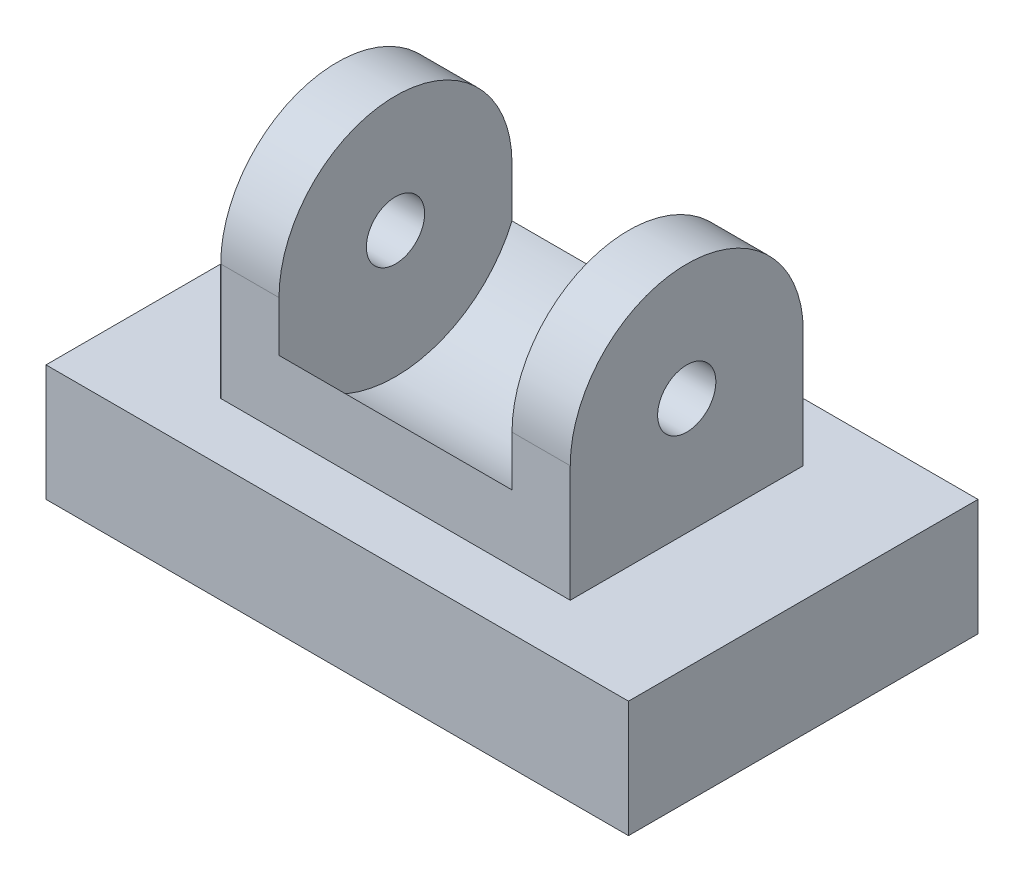
SolidWorks part; units mm, degrees
ref_plane "Plan de face" through (0, 0, 0) normal (0, 0, 1) x (1, 0, 0)
ref_plane "Plan de dessus" through (0, 0, 0) normal (0, 1, 0) x (1, 0, 0)
ref_plane "Plan de droite" through (0, 0, 0) normal (1, 0, 0) x (0, 0, -1)
sketch "Esquisse1" plane through (0, 0, 0) normal (0, 1, 0) x (1, 0, 0)
  line L1 (25, 15) -> (-25, 15)
  line L2 (25, 15) -> (25, -15)
  line L3 (25, -15) -> (-25, -15)
  line L4 (-25, 15) -> (-25, -15)
  line L5 (25, 15) -> (-25, -15) construction
  line L6 (25, -15) -> (-25, 15) construction
  point P0 (0, 0)
  dimension "D1" = 50
  dimension "D2" = 30
extrude "Boss.-Extru.1" add sketch "Esquisse1" along normal blind 10
sketch "Esquisse2" plane through (0, 0, 0) normal (1, 0, 0) x (0, 0, -1)
  line L0 (-15, 10) -> (15, 10) construction
  line L1 (-10, 20) -> (-10, 10)
  line L2 (10, 20) -> (10, 10)
  line L3 (10, 10) -> (-10, 10)
  arc A0 (10, 20) -> (-10, 20) centre (0, 20) ccw
  circle A1 centre (0, 20) radius 2.5
  dimension "D1" = 20
  dimension "D2" = 5
extrude "Boss.-Extru.2" add sketch "Esquisse2" along normal blind 15 and the other way blind 15
sketch "Esquisse3" plane through (0, 0, 0) normal (1, 0, 0) x (0, 0, -1)
  circle A0 centre (0, 20) radius 10.8841
  circle A1 centre (0, 20) radius 2.5
extrude "Enlèv. mat.-Extru.1" cut sketch "Esquisse3" against normal blind 10 and the other way blind 10
